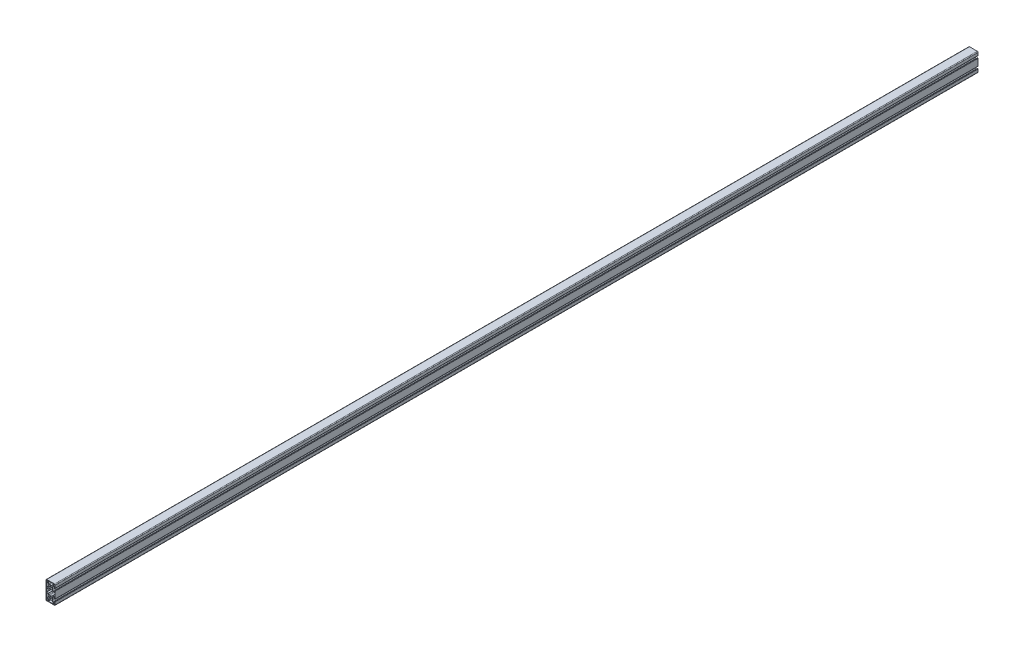
SolidWorks part; units mm, degrees
ref_plane "Front Plane" through (0, 0, 0) normal (0, 0, 1) x (1, 0, 0)
ref_plane "Top Plane" through (0, 0, 0) normal (0, 1, 0) x (1, 0, 0)
ref_plane "Right Plane" through (0, 0, 0) normal (1, 0, 0) x (0, 0, -1)
ref_plane "Plane1" through (0, 0, -4000) normal (0, 0, -1) x (-1, 0, 0)
sketch "Sketch1" plane through (0, 0, -4000) normal (0, 0, -1) x (-1, 0, 0)
  line L0 (18.3499, 55.5501) -> (18.3499, 52.5701)
  line L1 (17.7199, 51.9401) -> (13.2099, 51.9401)
  line L2 (11.9399, 53.2101) -> (11.9399, 57.7201)
  line L3 (12.5699, 58.3501) -> (15.5499, 58.3501)
  line L4 (18.3499, -12.5701) -> (18.3499, -15.5501)
  line L5 (15.5499, -18.3501) -> (12.5699, -18.3501)
  line L6 (11.9399, -17.7201) -> (11.9399, -13.2101)
  line L7 (13.2099, -11.9401) -> (17.7199, -11.9401)
  line L8 (18.3492, 27.1761) -> (18.3492, 12.8239)
  line L9 (17.4603, 11.935) -> (9.9702, 11.935)
  line L10 (9.3409, 11.6743) -> (6.5812, 8.9146)
  line L11 (3.2224, 7.5234) -> (-3.2224, 7.5234)
  line L12 (-6.5812, 8.9146) -> (-9.3409, 11.6743)
  line L13 (-9.9702, 11.935) -> (-17.4603, 11.935)
  line L14 (-18.3492, 12.8239) -> (-18.3492, 27.1761)
  line L15 (-17.4603, 28.065) -> (-9.9702, 28.065)
  line L16 (-9.3409, 28.3257) -> (-6.5812, 31.0854)
  line L17 (-3.2224, 32.4766) -> (3.2224, 32.4766)
  line L18 (6.5812, 31.0854) -> (9.3409, 28.3257)
  line L19 (9.9702, 28.065) -> (17.4603, 28.065)
  line L20 (18.3492, 9.3961) -> (18.3492, -9.3961)
  line L21 (17.4603, -10.285) -> (12.9871, -10.285)
  line L22 (12.3578, -10.0243) -> (9.0912, -6.7578)
  line L23 (7.7, -3.399) -> (7.7, 3.399)
  line L24 (9.0912, 6.7578) -> (12.3578, 10.0243)
  line L25 (12.9871, 10.285) -> (17.4603, 10.285)
  line L26 (18.3492, 49.3961) -> (18.3492, 30.6039)
  line L27 (17.4603, 29.715) -> (12.9871, 29.715)
  line L28 (12.3578, 29.9757) -> (9.0912, 33.2422)
  line L29 (7.7, 36.601) -> (7.7, 43.399)
  line L30 (9.0912, 46.7578) -> (12.3578, 50.0243)
  line L31 (12.9871, 50.285) -> (17.4603, 50.285)
  line L32 (10.2899, 57.4612) -> (10.2899, 52.992)
  line L33 (10.0292, 52.3627) -> (6.5812, 48.9146)
  line L34 (3.2224, 47.5234) -> (-3.2224, 47.5234)
  line L35 (-6.5812, 48.9146) -> (-10.0292, 52.3627)
  line L36 (-10.2899, 52.992) -> (-10.2899, 57.4612)
  line L37 (-9.401, 58.3501) -> (9.401, 58.3501)
  line L38 (10.2899, -12.992) -> (10.2899, -17.4216)
  line L39 (9.401, -18.3105) -> (-9.401, -18.3105)
  line L40 (-10.2899, -17.4216) -> (-10.2899, -12.992)
  line L41 (-10.0292, -12.3627) -> (-6.5812, -8.9146)
  line L42 (-3.2224, -7.5234) -> (3.2224, -7.5234)
  line L43 (6.5812, -8.9146) -> (10.0292, -12.3627)
  line L44 (-11.9399, 57.7201) -> (-11.9399, 53.2101)
  line L45 (-13.2099, 51.9401) -> (-17.7199, 51.9401)
  line L46 (-18.3499, 52.5701) -> (-18.3499, 55.5501)
  line L47 (-15.5499, 58.3501) -> (-12.5699, 58.3501)
  line L48 (-11.9399, -13.2101) -> (-11.9399, -17.7201)
  line L49 (-12.5699, -18.3501) -> (-15.5499, -18.3501)
  line L50 (-18.3499, -15.5501) -> (-18.3499, -12.5701)
  line L51 (-17.7199, -11.9401) -> (-13.2099, -11.9401)
  line L52 (20, -16.83) -> (20, 56.83)
  line L53 (16.83, 60) -> (-16.83, 60)
  line L54 (-20, 56.83) -> (-20, 45.5403)
  line L55 (-18.5197, 44.06) -> (-17.8048, 44.06)
  line L56 (-15.94, 45.9248) -> (-15.94, 47.2807)
  line L57 (-15.94, 47.2807) -> (-16.7, 47.2807)
  line L58 (-16.7, 47.2807) -> (-16.7, 48.9483)
  line L59 (-15.3633, 50.285) -> (-12.9871, 50.285)
  line L60 (-12.3578, 50.0243) -> (-9.0912, 46.7578)
  line L61 (-7.7, 43.399) -> (-7.7, 36.601)
  line L62 (-9.0912, 33.2422) -> (-12.3578, 29.9757)
  line L63 (-12.9871, 29.715) -> (-15.3633, 29.715)
  line L64 (-16.7, 31.0517) -> (-16.7, 32.7193)
  line L65 (-16.7, 32.7193) -> (-15.94, 32.7193)
  line L66 (-15.94, 32.7193) -> (-15.94, 34.0752)
  line L67 (-17.8048, 35.94) -> (-18.5197, 35.94)
  line L68 (-20, 34.4597) -> (-20, 5.5403)
  line L69 (-18.5197, 4.06) -> (-17.8048, 4.06)
  line L70 (-15.94, 5.9248) -> (-15.94, 7.2807)
  line L71 (-15.94, 7.2807) -> (-16.7, 7.2807)
  line L72 (-16.7, 7.2807) -> (-16.7, 9.015)
  line L73 (-15.43, 10.285) -> (-12.9871, 10.285)
  line L74 (-12.3578, 10.0243) -> (-9.0912, 6.7578)
  line L75 (-7.7, 3.399) -> (-7.7, -3.399)
  line L76 (-9.0912, -6.7578) -> (-12.3578, -10.0243)
  line L77 (-12.9871, -10.285) -> (-15.3633, -10.285)
  line L78 (-16.7, -8.9483) -> (-16.7, -7.2807)
  line L79 (-16.7, -7.2807) -> (-15.94, -7.2807)
  line L80 (-15.94, -7.2807) -> (-15.94, -5.9248)
  line L81 (-17.8048, -4.06) -> (-18.5197, -4.06)
  line L82 (-20, -5.5403) -> (-20, -16.83)
  line L83 (-16.83, -20) -> (16.83, -20)
  arc A0 (15.5499, 58.3501) -> (18.3499, 55.5501) centre (15.5499, 55.5501) cw
  arc A1 (18.3499, 52.5701) -> (17.7199, 51.9401) centre (17.7199, 52.5701) cw
  arc A2 (13.2099, 51.9401) -> (11.9399, 53.2101) centre (13.2099, 53.2101) cw
  arc A3 (11.9399, 57.7201) -> (12.5699, 58.3501) centre (12.5699, 57.7201) cw
  arc A4 (18.3499, -15.5501) -> (15.5499, -18.3501) centre (15.5499, -15.5501) cw
  arc A5 (12.5699, -18.3501) -> (11.9399, -17.7201) centre (12.5699, -17.7201) cw
  arc A6 (11.9399, -13.2101) -> (13.2099, -11.9401) centre (13.2099, -13.2101) cw
  arc A7 (17.7199, -11.9401) -> (18.3499, -12.5701) centre (17.7199, -12.5701) cw
  arc A8 (18.3492, 12.8239) -> (17.4603, 11.935) centre (17.4603, 12.8239) cw
  arc A9 (9.9702, 11.935) -> (9.3409, 11.6743) centre (9.9702, 11.045) ccw
  arc A10 (6.5812, 8.9146) -> (3.2224, 7.5234) centre (3.2224, 12.2734) cw
  arc A11 (-3.2224, 7.5234) -> (-6.5812, 8.9146) centre (-3.2224, 12.2734) cw
  arc A12 (-9.3409, 11.6743) -> (-9.9702, 11.935) centre (-9.9702, 11.045) ccw
  arc A13 (-17.4603, 11.935) -> (-18.3492, 12.8239) centre (-17.4603, 12.8239) cw
  arc A14 (-18.3492, 27.1761) -> (-17.4603, 28.065) centre (-17.4603, 27.1761) cw
  arc A15 (-9.9702, 28.065) -> (-9.3409, 28.3257) centre (-9.9702, 28.955) ccw
  arc A16 (-6.5812, 31.0854) -> (-3.2224, 32.4766) centre (-3.2224, 27.7266) cw
  arc A17 (3.2224, 32.4766) -> (6.5812, 31.0854) centre (3.2224, 27.7266) cw
  arc A18 (9.3409, 28.3257) -> (9.9702, 28.065) centre (9.9702, 28.955) ccw
  arc A19 (17.4603, 28.065) -> (18.3492, 27.1761) centre (17.4603, 27.1761) cw
  arc A20 (18.3492, -9.3961) -> (17.4603, -10.285) centre (17.4603, -9.3961) cw
  arc A21 (12.9871, -10.285) -> (12.3578, -10.0243) centre (12.9871, -9.395) cw
  arc A22 (9.0912, -6.7578) -> (7.7, -3.399) centre (12.45, -3.399) cw
  arc A23 (7.7, 3.399) -> (9.0912, 6.7578) centre (12.45, 3.399) cw
  arc A24 (12.3578, 10.0243) -> (12.9871, 10.285) centre (12.9871, 9.395) cw
  arc A25 (17.4603, 10.285) -> (18.3492, 9.3961) centre (17.4603, 9.3961) cw
  arc A26 (18.3492, 30.6039) -> (17.4603, 29.715) centre (17.4603, 30.6039) cw
  arc A27 (12.9871, 29.715) -> (12.3578, 29.9757) centre (12.9871, 30.605) cw
  arc A28 (9.0912, 33.2422) -> (7.7, 36.601) centre (12.45, 36.601) cw
  arc A29 (7.7, 43.399) -> (9.0912, 46.7578) centre (12.45, 43.399) cw
  arc A30 (12.3578, 50.0243) -> (12.9871, 50.285) centre (12.9871, 49.395) cw
  arc A31 (17.4603, 50.285) -> (18.3492, 49.3961) centre (17.4603, 49.3961) cw
  arc A32 (10.2899, 52.992) -> (10.0292, 52.3627) centre (9.3999, 52.992) cw
  arc A33 (6.5812, 48.9146) -> (3.2224, 47.5234) centre (3.2224, 52.2734) cw
  arc A34 (-3.2224, 47.5234) -> (-6.5812, 48.9146) centre (-3.2224, 52.2734) cw
  arc A35 (-10.0292, 52.3627) -> (-10.2899, 52.992) centre (-9.3999, 52.992) cw
  arc A36 (-10.2899, 57.4612) -> (-9.401, 58.3501) centre (-9.401, 57.4612) cw
  arc A37 (9.401, 58.3501) -> (10.2899, 57.4612) centre (9.401, 57.4612) cw
  arc A38 (10.0292, -12.3627) -> (10.2899, -12.992) centre (9.3999, -12.992) cw
  arc A39 (10.2899, -17.4216) -> (9.401, -18.3105) centre (9.401, -17.4216) cw
  arc A40 (-9.401, -18.3105) -> (-10.2899, -17.4216) centre (-9.401, -17.4216) cw
  arc A41 (-10.2899, -12.992) -> (-10.0292, -12.3627) centre (-9.3999, -12.992) cw
  arc A42 (-6.5812, -8.9146) -> (-3.2224, -7.5234) centre (-3.2224, -12.2734) cw
  arc A43 (3.2224, -7.5234) -> (6.5812, -8.9146) centre (3.2224, -12.2734) cw
  circle A44 centre (0, 40) radius 3.405
  circle A45 centre (0, 0) radius 3.405
  arc A46 (-11.9399, 53.2101) -> (-13.2099, 51.9401) centre (-13.2099, 53.2101) cw
  arc A47 (-17.7199, 51.9401) -> (-18.3499, 52.5701) centre (-17.7199, 52.5701) cw
  arc A48 (-18.3499, 55.5501) -> (-15.5499, 58.3501) centre (-15.5499, 55.5501) cw
  arc A49 (-12.5699, 58.3501) -> (-11.9399, 57.7201) centre (-12.5699, 57.7201) cw
  arc A50 (-13.2099, -11.9401) -> (-11.9399, -13.2101) centre (-13.2099, -13.2101) cw
  arc A51 (-11.9399, -17.7201) -> (-12.5699, -18.3501) centre (-12.5699, -17.7201) cw
  arc A52 (-15.5499, -18.3501) -> (-18.3499, -15.5501) centre (-15.5499, -15.5501) cw
  arc A53 (-18.3499, -12.5701) -> (-17.7199, -11.9401) centre (-17.7199, -12.5701) cw
  arc A54 (20, 56.83) -> (16.83, 60) centre (16.83, 56.83) ccw
  arc A55 (-16.83, 60) -> (-20, 56.83) centre (-16.83, 56.83) ccw
  arc A56 (-20, 45.5403) -> (-18.5197, 44.06) centre (-18.5197, 45.5403) ccw
  arc A57 (-17.8048, 44.06) -> (-15.94, 45.9248) centre (-17.8048, 45.9248) ccw
  arc A58 (-16.7, 48.9483) -> (-15.3633, 50.285) centre (-15.3633, 48.9483) cw
  arc A59 (-12.9871, 50.285) -> (-12.3578, 50.0243) centre (-12.9871, 49.395) cw
  arc A60 (-9.0912, 46.7578) -> (-7.7, 43.399) centre (-12.45, 43.399) cw
  arc A61 (-7.7, 36.601) -> (-9.0912, 33.2422) centre (-12.45, 36.601) cw
  arc A62 (-12.3578, 29.9757) -> (-12.9871, 29.715) centre (-12.9871, 30.605) cw
  arc A63 (-15.3633, 29.715) -> (-16.7, 31.0517) centre (-15.3633, 31.0517) cw
  arc A64 (-15.94, 34.0752) -> (-17.8048, 35.94) centre (-17.8048, 34.0752) ccw
  arc A65 (-18.5197, 35.94) -> (-20, 34.4597) centre (-18.5197, 34.4597) ccw
  arc A66 (-20, 5.5403) -> (-18.5197, 4.06) centre (-18.5197, 5.5403) ccw
  arc A67 (-17.8048, 4.06) -> (-15.94, 5.9248) centre (-17.8048, 5.9248) ccw
  arc A68 (-16.7, 9.015) -> (-15.43, 10.285) centre (-15.43, 9.015) cw
  arc A69 (-12.9871, 10.285) -> (-12.3578, 10.0243) centre (-12.9871, 9.395) cw
  arc A70 (-9.0912, 6.7578) -> (-7.7, 3.399) centre (-12.45, 3.399) cw
  arc A71 (-7.7, -3.399) -> (-9.0912, -6.7578) centre (-12.45, -3.399) cw
  arc A72 (-12.3578, -10.0243) -> (-12.9871, -10.285) centre (-12.9871, -9.395) cw
  arc A73 (-15.3633, -10.285) -> (-16.7, -8.9483) centre (-15.3633, -8.9483) cw
  arc A74 (-15.94, -5.9248) -> (-17.8048, -4.06) centre (-17.8048, -5.9248) ccw
  arc A75 (-18.5197, -4.06) -> (-20, -5.5403) centre (-18.5197, -5.5403) ccw
  arc A76 (-20, -16.83) -> (-16.83, -20) centre (-16.83, -16.83) ccw
  arc A77 (16.83, -20) -> (20, -16.83) centre (16.83, -16.83) ccw
extrude "Boss-Extrude1" add sketch "Sketch1" against normal blind 4000
